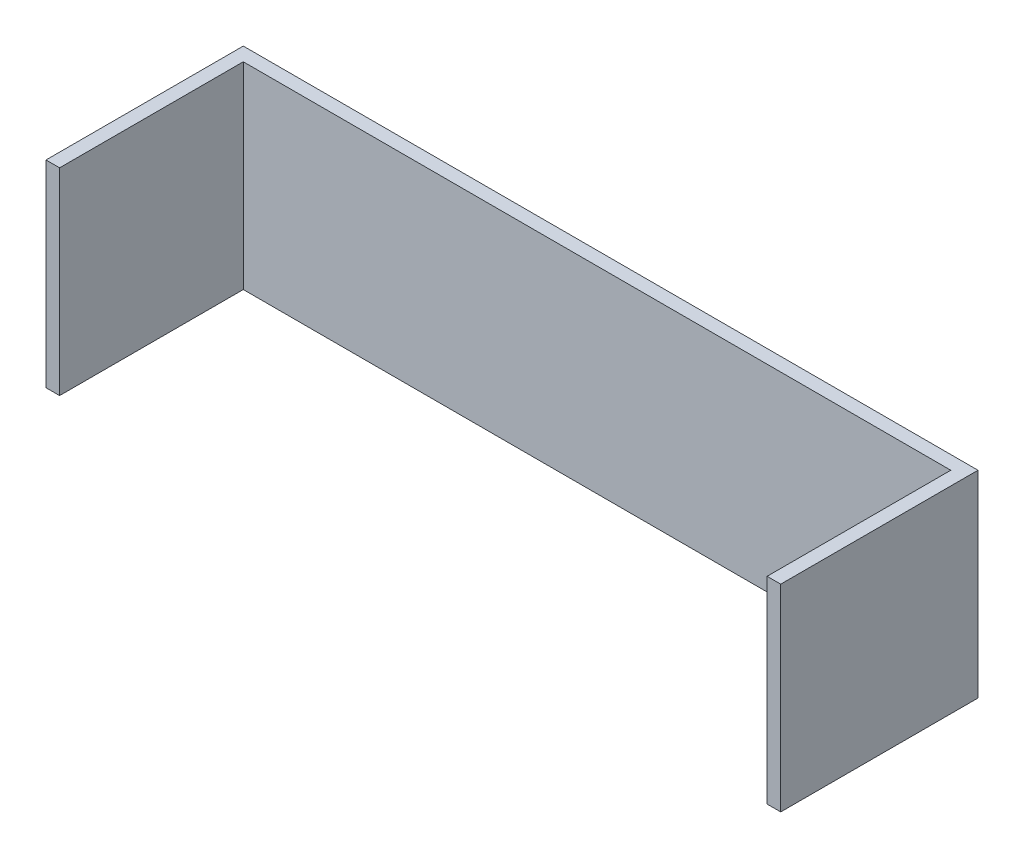
SolidWorks part; units mm, degrees
ref_plane "Front Plane" through (0, 0, 0) normal (0, 0, 1) x (1, 0, 0)
ref_plane "Top Plane" through (0, 0, 0) normal (0, 1, 0) x (1, 0, 0)
ref_plane "Right Plane" through (0, 0, 0) normal (1, 0, 0) x (0, 0, -1)
sketch "Sketch1" plane through (0, 0, 0) normal (0, 1, 0) x (1, 0, 0)
  line L0 (0, 0) -> (-540, 0)
  line L1 (-540, 0) -> (-540, -145)
  line L2 (-540, -145) -> (-530, -145)
  line L3 (-530, -145) -> (-530, -10)
  line L4 (-530, -10) -> (-10, -10)
  line L5 (-10, -10) -> (-10, -145)
  line L6 (-10, -145) -> (0, -145)
  line L7 (0, -145) -> (0, 0)
  point P3 (0, 0)
  dimension "D1" = 540
  dimension "D2" = 145
  dimension "D3" = 10
  dimension "D4" = 10
  dimension "D5" = 10
extrude "Boss-Extrude1" add sketch "Sketch1" along normal blind 145
